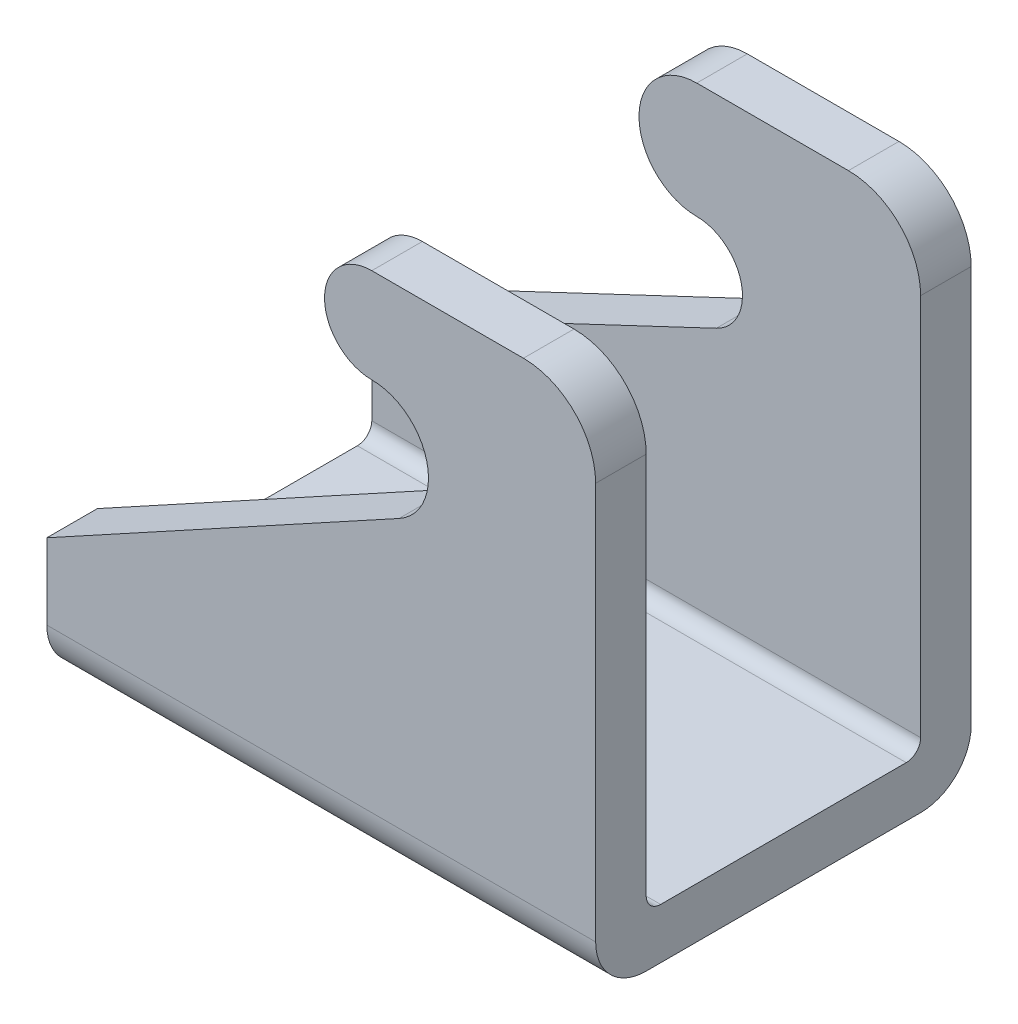
SolidWorks part; units mm, degrees
ref_plane "Front Plane" through (0, 0, 0) normal (0, 0, 1) x (1, 0, 0)
ref_plane "Top Plane" through (0, 0, 0) normal (0, 1, 0) x (1, 0, 0)
ref_plane "Right Plane" through (0, 0, 0) normal (1, 0, 0) x (0, 0, -1)
ref_plane "Plane1" through (0, 0, 13) normal (0, 0, 1) x (1, 0, 0)
sketch "Sketch1" plane through (0, 0, 13) normal (0, 0, 1) x (1, 0, 0)
  line L0 (0, 36) -> (0, 0)
  line L1 (0, 0) -> (38, 0)
  line L2 (38, 0) -> (38, 36)
  line L3 (38, 36) -> (0, 36)
extrude "Boss-Extrude1" add sketch "Sketch1" against normal blind 26
sketch "Sketch2" plane through (38, 0, 0) normal (1, 0, 0) x (0, 0, -1)
  line L0 (-9.5, 36) -> (-9.5, 3.5)
  line L1 (-9.5, 3.5) -> (9.5, 3.5)
  line L2 (9.5, 3.5) -> (9.5, 36)
  line L3 (9.5, 36) -> (-9.5, 36)
extrude "Cut-Extrude1" cut sketch "Sketch2" against normal through all
sketch "Sketch3" plane through (0, 0, 13) normal (0, 0, 1) x (1, 0, 0)
  line L0 (22.5, 36) -> (0, 36)
  line L1 (0, 36) -> (0, 8.7343)
  line L2 (0, 8.7343) -> (24.3851, 22.0836)
  line L3 (0, 36) -> (0, 0) construction
  arc A0 (22.5, 29.4528) -> (22.5, 36) centre (22.5, 32.7264) cw
  arc A1 (24.3851, 22.0836) -> (22.5, 29.4528) centre (22.5, 25.5271) ccw
  dimension "D1" = 22.5
  dimension "D2" = 3.2736
extrude "Cut-Extrude2" cut sketch "Sketch3" against normal up to next
sketch "Sketch4" plane through (0, 0, -13) normal (0, 0, -1) x (-1, 0, 0)
  line L0 (-23.8525, 21.9726) -> (0, 10.7)
  line L1 (0, 10.7) -> (0, 36)
  line L2 (0, 36) -> (-22.5, 36)
  line L3 (0, 36) -> (0, 0) construction
  arc A0 (-22.5, 28) -> (-23.8525, 21.9726) centre (-22.5, 24.8346) ccw
  arc A1 (-22.5, 36) -> (-22.5, 28) centre (-22.5, 32) cw
  dimension "D1" = 22.5
extrude "Cut-Extrude3" cut sketch "Sketch4" against normal up to next
fillet "Fillet1" radius 1 2 edges at (19, 3.5, -9.5) (19, 3.5, 9.5)
fillet "Fillet2" radius 3.5 2 edges at (19, 0, 13) (19, 0, -13)
fillet "Fillet3" radius 5 2 edges at (38, 36, 11.25) (38, 36, -11.25)
